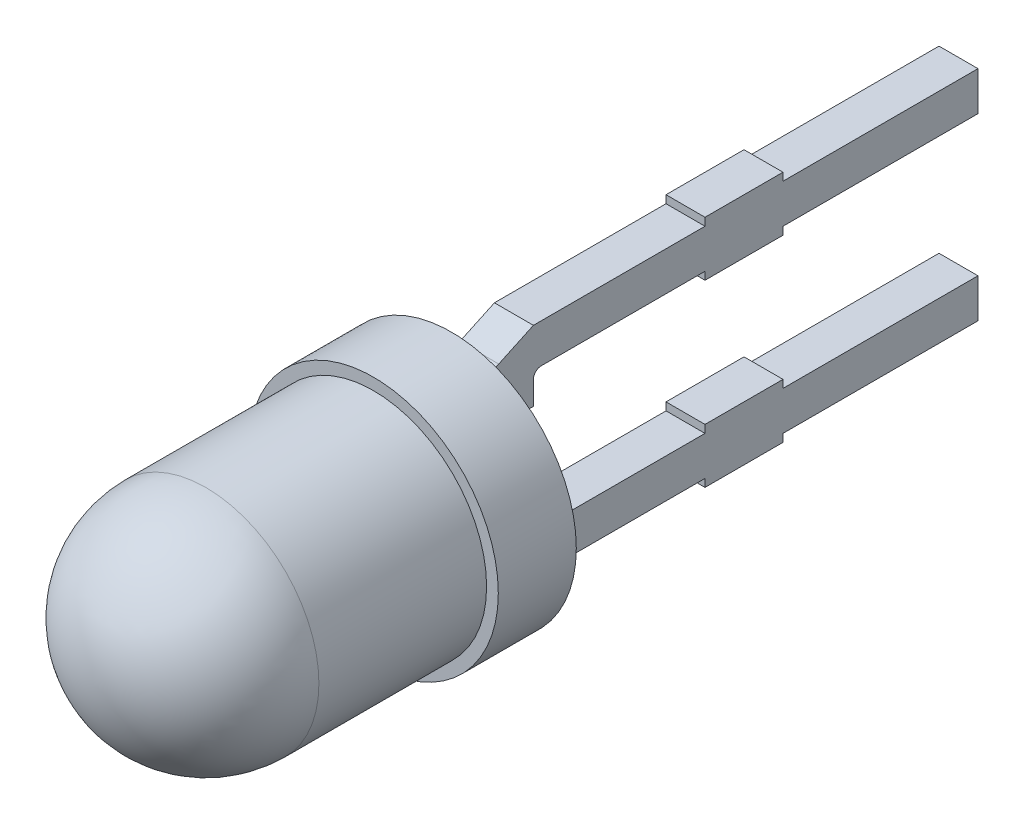
SolidWorks part; units mm, degrees
ref_plane "Front" through (0, 0, 0) normal (0, 0, 1) x (1, 0, 0)
ref_plane "Top" through (0, 0, 0) normal (0, 1, 0) x (1, 0, 0)
ref_plane "Right" through (0, 0, 0) normal (1, 0, 0) x (0, 0, -1)
sketch "Sketch1" plane through (0, 0, 0) normal (1, 0, 0) x (0, 0, -1)
  line L0 (0, 0) -> (76.2974, 0) construction
  line L1 (0, 1.45) -> (2.15, 1.45)
  line L2 (2.15, 1.45) -> (2.15, 1.6)
  line L3 (2.15, 1.6) -> (3.15, 1.6)
  line L4 (3.15, 1.6) -> (3.15, 0)
  line L5 (3.15, 0) -> (-1.45, 0)
  arc A0 (0, 1.45) -> (-1.45, 0) centre (0, 0) ccw
  dimension "D1" = 1.45
  dimension "D2" = 4.6
  dimension "D3" = 1
  dimension "D4" = 1.6
revolve "Revolve1" add sketch "Sketch1" angle 360 about L0
sketch "Sketch2" plane through (0, 0, 0) normal (1, 0, 0) x (0, 0, -1)
  line L0 (3.15, -1.6) -> (3.15, 1.6) construction
  line L1 (3.15, -1.6) -> (3.15, 1.6) construction
  line L2 (3.15, 1.027) -> (3.95, 1.4)
  line L3 (3.95, 1.4) -> (6.15, 1.4)
  line L4 (6.15, 1.4) -> (6.15, 1.5)
  line L5 (6.15, 1.5) -> (7.15, 1.5)
  line L6 (7.15, 1.5) -> (7.15, 1.4)
  line L7 (7.15, 1.4) -> (30.15, 1.4)
  line L8 (30.15, 1.4) -> (30.15, 0.9)
  line L9 (30.15, 0.9) -> (7.15, 0.9)
  line L10 (7.15, 0.9) -> (7.15, 0.8)
  line L11 (7.15, 0.8) -> (6.15, 0.8)
  line L12 (6.15, 0.8) -> (6.15, 0.9)
  line L13 (6.15, 0.9) -> (4.05, 0.9)
  line L14 (3.95, 0.8) -> (3.95, 0.5)
  line L15 (3.95, 0.5) -> (3.15, 0.5)
  line L16 (3.15, 0) -> (7.9733, 0) construction
  line L17 (3.15, 1.027) -> (3.15, 0.5)
  line L18 (3.95, -0.8) -> (3.95, -0.5)
  line L19 (6.15, -0.9) -> (4.05, -0.9)
  line L20 (6.15, -0.8) -> (6.15, -0.9)
  line L21 (7.15, -0.8) -> (6.15, -0.8)
  line L22 (7.15, -0.9) -> (7.15, -0.8)
  line L23 (30.15, -0.9) -> (7.15, -0.9)
  line L24 (30.15, -1.4) -> (30.15, -0.9)
  line L25 (7.15, -1.4) -> (30.15, -1.4)
  line L26 (7.15, -1.5) -> (7.15, -1.4)
  line L27 (6.15, -1.5) -> (7.15, -1.5)
  line L28 (6.15, -1.4) -> (6.15, -1.5)
  line L29 (3.95, -1.4) -> (6.15, -1.4)
  line L30 (3.15, -1.027) -> (3.95, -1.4)
  line L31 (3.15, -1.027) -> (3.15, -0.5)
  line L32 (3.95, -0.5) -> (3.15, -0.5)
  arc A0 (4.05, 0.9) -> (3.95, 0.8) centre (4.05, 0.8) ccw
  arc A1 (4.05, -0.9) -> (3.95, -0.8) centre (4.05, -0.8) cw
  point P19 (3.15, 0)
  dimension "D1" = 0.5
  dimension "D2" = 0.7
  dimension "D3" = 1.4
  dimension "D4" = 0.8
  dimension "D5" = 27
  dimension "D6" = 115
  dimension "D7" = 4
  dimension "D8" = 1
  dimension "D9" = 0.5
  dimension "D10" = 0.1
extrude "Extrude1" add sketch "Sketch2" along normal mid plane 0.5
fillet "Fillet1" radius 0.25 8 edges at (0, -0.5, -3.15) (0, -1.027, -3.15) (-0.25, -0.7635, -3.15) (0, 0.5, -3.15) (-0.25, 0.7635, -3.15) (0, 1.027, -3.15) (0.25, 0.7635, -3.15) (0.25, -0.7635, -3.15)
sketch "Sketch3" plane through (0, 0, 0) normal (1, 0, 0) x (0, 0, -1)
  line L0 (18.15, 1.4) -> (18.15, -1.4)
  line L1 (30.15, 1.4) -> (7.15, 1.4) construction
  line L2 (7.15, -1.4) -> (30.15, -1.4) construction
  line L3 (18.15, -1.4) -> (31.0324, -1.4)
  line L4 (31.0324, -1.4) -> (31.0324, 1.4)
  line L5 (31.0324, 1.4) -> (18.15, 1.4)
  line L6 (3.15, -1.6) -> (3.15, 1.6) construction
  dimension "D1" = 15
extrude "Cut-Extrude1" cut sketch "Sketch3" against normal through all both and the other way through all
sketch "Sketch4" plane through (0, 0, 0) normal (1, 0, 0) x (0, 0, -1)
  line L0 (3.15, -1.6) -> (3.15, 1.6) construction
  line L1 (9.65, 3.0934) -> (21.3964, 3.0934)
  line L2 (9.65, 3.0934) -> (9.65, -2.7205)
  line L3 (9.65, -2.7205) -> (21.3964, -2.7205)
  line L4 (21.3964, 3.0934) -> (21.3964, -2.7205)
  dimension "D1" = 6.5
extrude "Cut-Extrude2" cut sketch "Sketch4" against normal through all both and the other way through all
